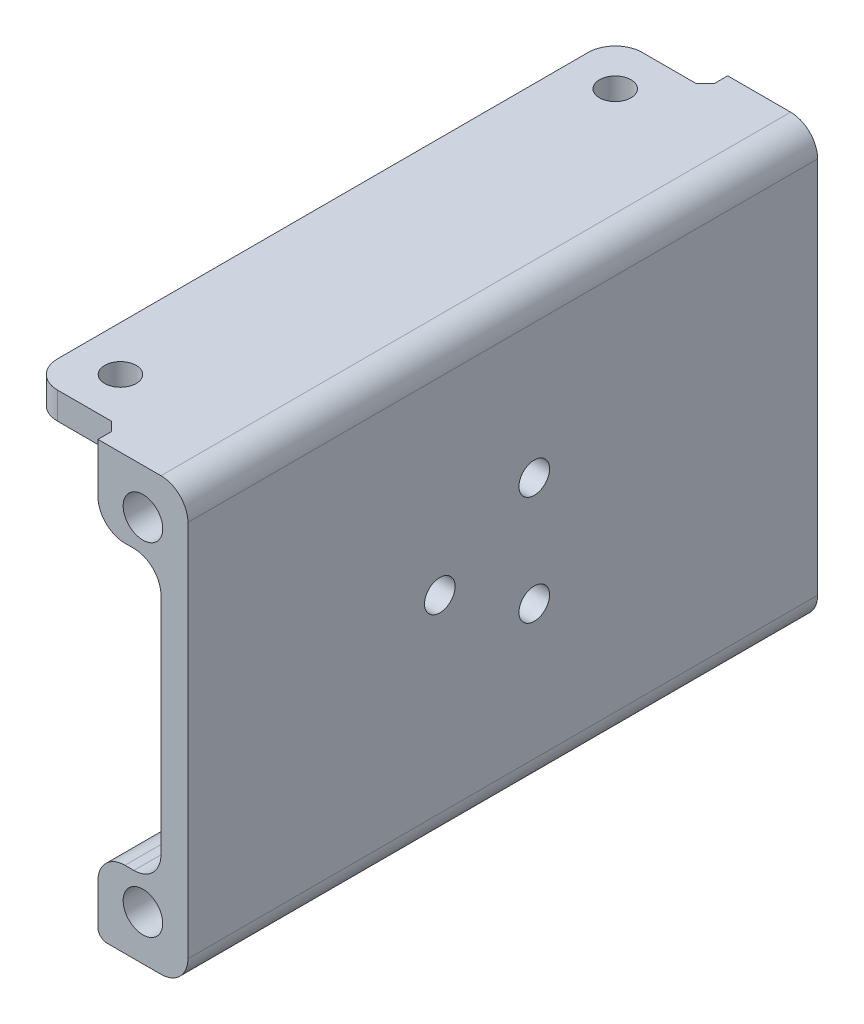
SolidWorks part; units mm, degrees
ref_plane "Front Plane" through (0, 0, 0) normal (0, 0, 1) x (1, 0, 0)
ref_plane "Top Plane" through (0, 0, 0) normal (0, 1, 0) x (1, 0, 0)
ref_plane "Right Plane" through (0, 0, 0) normal (1, 0, 0) x (0, 0, -1)
sketch "Sketch1" plane through (0, 0, 0) normal (0, 0, 1) x (1, 0, 0)
  line L0 (54, -19) -> (54, 19) construction
  line L1 (49, 24) -> (49, 18.5)
  line L2 (49, 24) -> (56, 24)
  line L4 (49, -24) -> (56, -24)
  line L5 (59, 21) -> (59, -21)
  line L6 (49, 24) -> (59, -24) construction
  line L7 (49, -24) -> (59, 24) construction
  line L8 (52, 15.5) -> (53, 15.5)
  line L9 (56, 12.5) -> (56, -12.5)
  line L10 (53, -15.5) -> (52, -15.5)
  line L11 (49, -18.5) -> (49, -24)
  arc A0 (56, -24) -> (59, -21) centre (56, -21) ccw
  arc A1 (59, 21) -> (56, 24) centre (56, 21) ccw
  arc A2 (56, -12.5) -> (53, -15.5) centre (53, -12.5) cw
  arc A3 (56, 12.5) -> (53, 15.5) centre (53, 12.5) ccw
  arc A4 (52, -15.5) -> (49, -18.5) centre (52, -18.5) ccw
  arc A5 (52, 15.5) -> (49, 18.5) centre (52, 18.5) cw
  point P4 (54, 0)
  dimension "D3" = 3
  dimension "D4" = 3
  dimension "D5" = 3
  dimension "D6" = 3
  dimension "D1" = 10
  dimension "D2" = 48
  dimension "D7" = 7
  dimension "D8" = 5.5
extrude "Boss-Extrude1" add sketch "Sketch1" along normal blind 70
sketch "Sketch2" plane through (0, 0, 0) normal (0, 0, -1) x (-1, 0, 0)
  circle A0 centre (-54, -19) radius 2.2
  circle A1 centre (-54, 19) radius 2.2
  dimension "D1" = 4.4
ref_plane "Plane1" through (0, 0, 35) normal (0, 0, -1) x (-1, 0, 0)
extrude "Cut-Extrude1" cut sketch "Sketch2" against normal blind 5.3
mirror "Mirror1" about plane through (0, 0, 35) normal (0, 0, -1) of "Cut-Extrude1"
fillet "Fillet1" radius 1 1 edges at (49, -24, 35)
sketch "Sketch4" plane through (59, 0, 0) normal (1, 0, 0) x (0, 0, -1)
  line L0 (-42, 0) -> (-35, 0) construction
  line L1 (-35, 0) -> (-31.5, 6.0622) construction
  line L2 (-35, 0) -> (-31.5, -6.0622) construction
  line L4 (-70, 0) -> (-35, 0) construction
  line L5 (-70, -21) -> (-70, 21) construction
  circle A0 centre (-42, 0) radius 1.7
  circle A1 centre (-31.5, 6.0622) radius 1.7
  circle A2 centre (-31.5, -6.0622) radius 1.7
  circle A3 centre (-35, 0) radius 7 construction
  dimension "D1" = 14
  dimension "D2" = 3.4
  dimension "D3" = 120
  dimension "D4" = 120
  dimension "D5" = 35
extrude "Cut-Extrude3" cut sketch "Sketch4" against normal blind 10
sketch "Sketch5" plane through (0, 24, 0) normal (0, -1, 0) x (1, 0, 0)
  line L0 (49, 35) -> (39, 35) construction
  line L1 (49, 70) -> (49, 0) construction
  line L2 (44, 35) -> (44, 62.5) construction
  line L3 (49, 2.5) -> (42, 2.5)
  line L4 (49, 2.5) -> (49, 67.5)
  line L5 (49, 67.5) -> (42, 67.5)
  line L6 (39, 5.5) -> (39, 64.5)
  line L7 (49, 2.5) -> (39, 67.5) construction
  line L8 (49, 67.5) -> (39, 2.5) construction
  arc A0 (39, 5.5) -> (42, 2.5) centre (42, 5.5) ccw
  arc A1 (39, 64.5) -> (42, 67.5) centre (42, 64.5) cw
  circle A2 centre (44, 62.5) radius 1.75
  circle A3 centre (44, 7.5) radius 1.75
  point P4 (44, 35)
  dimension "D3" = 3
  dimension "D5" = 3.5
  dimension "D1" = 65
  dimension "D2" = 10
  dimension "D4" = 5
extrude "Boss-Extrude2" add sketch "Sketch5" along normal blind 3
chamfer "Chamfer1" distance 1 angle 45 3 edges at (49, 22.5, 2.5) (49, 21, 35) (49, 22.5, 67.5)
